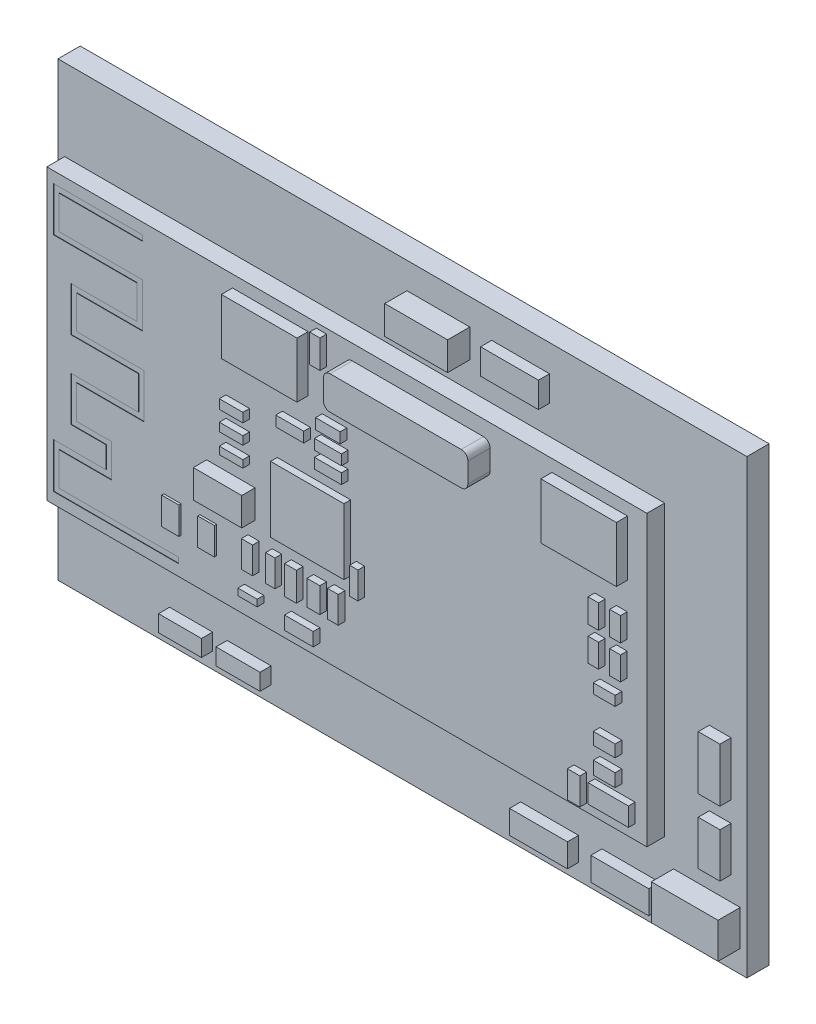
SolidWorks part; units mm, degrees
ref_plane "前视基准面" through (0, 0, 0) normal (0, 0, 1) x (1, 0, 0)
ref_plane "上视基准面" through (0, 0, 0) normal (0, 1, 0) x (1, 0, 0)
ref_plane "右视基准面" through (0, 0, 0) normal (1, 0, 0) x (0, 0, -1)
sketch "草图1" plane through (0, 0, 0) normal (0, 0, 1) x (1, 0, 0)
  line L1 (-24, -12) -> (24, -12)
  line L2 (-24, -12) -> (-24, 12)
  line L3 (-24, 12) -> (24, 12)
  line L4 (24, -12) -> (24, 12)
  line L5 (-24, -12) -> (24, 12) construction
  line L6 (-24, 12) -> (24, -12) construction
  circle A0 centre (8, 8) radius 2.1
  circle A1 centre (8, -8) radius 2.1
  point P0 (0, 0)
  dimension "D3" = 4
  dimension "D1" = 24
  dimension "D2" = 48
  dimension "D4" = 4
  dimension "D5" = 16
  dimension "D6" = 16
extrude "凸台-拉伸1" add sketch "草图1" along normal mid plane 1.6
fillet "圆角1" radius 3 4 edges at (24, 12, 0) (24, -12, 0) (-24, 12, 0) (-24, -12, 0)
sketch "草图7" plane through (0, 0, -0.8) normal (0, 0, -1) x (-1, 0, 0)
  circle A0 centre (-8, 8) radius 2.1
  circle A1 centre (-8, 8) radius 3
  circle A2 centre (-8, -8) radius 2.1
  circle A3 centre (-8, -8) radius 3
extrude "凸台-拉伸4" add sketch "草图7" along normal blind 0.01
mirror "镜向1" about plane through (0, 0, 0) normal (0, 0, 1) of "凸台-拉伸4"
sketch "草图8" plane through (0, 0, 0.8) normal (0, 0, 1) x (1, 0, 0)
  line L0 (24, -9) -> (24, 9) construction
  line L1 (-21, -12) -> (21, -12) construction
  circle A0 centre (21.46, 7) radius 0.9
  circle A1 centre (21.46, -5) radius 0.9
  dimension "D1" = 1.8
  dimension "D2" = 1.8
  dimension "D3" = 7
  dimension "D4" = 12
  dimension "D5" = 2.54
extrude "切除-拉伸4" cut sketch "草图8" against normal up to next
sketch "草图9" plane through (0, 0, 0.8) normal (0, 0, 1) x (1, 0, 0)
  line L0 (-24, 9) -> (-24, -9) construction
  line L1 (3.1, -6.5) -> (-23.9, -6.5)
  line L2 (3.1, -6.5) -> (3.1, 6.5)
  line L3 (3.1, 6.5) -> (-23.9, 6.5)
  line L4 (-23.9, -6.5) -> (-23.9, 6.5)
  line L5 (3.1, -6.5) -> (-23.9, 6.5) construction
  line L6 (3.1, 6.5) -> (-23.9, -6.5) construction
  point P0 (-10.4, 0)
  dimension "D1" = 0.1
  dimension "D2" = 27
  dimension "D3" = 13
  dimension "D4" = 0
extrude "凸台-拉伸5" add sketch "草图9" along normal blind 0.8
sketch "草图12" plane through (0, 0, 1.6) normal (0, 0, 1) x (1, 0, 0)
  line L0 (-19.605, 6) -> (-23.605, 6)
  line L1 (-23.605, 6) -> (-23.605, 4)
  line L2 (-23.605, 4) -> (-19.855, 4)
  line L3 (-19.855, 4) -> (-19.855, 2.5)
  line L4 (-19.855, 2.5) -> (-22.8189, 2.5)
  line L5 (-22.8189, 2.5) -> (-22.8189, 0.5)
  line L6 (-22.8189, 0.5) -> (-19.7832, 0.5)
  line L7 (-19.7832, 0.5) -> (-19.7832, -1)
  line L8 (-19.7832, -1) -> (-22.8189, -1)
  line L9 (-22.8189, -1) -> (-22.8189, -3)
  line L10 (-22.8189, -3) -> (-21.2355, -3)
  line L11 (-21.2355, -3) -> (-21.2355, -3.9734)
  line L12 (-21.2355, -3.9734) -> (-23.605, -3.9734)
  line L13 (-23.605, -3.9734) -> (-23.605, -6)
  line L14 (-23.605, -6) -> (-17.9828, -6)
  line L15 (-17.9828, -6) -> (-17.9828, -5.75)
  line L16 (-17.9828, -5.75) -> (-23.355, -5.75)
  line L17 (-23.355, -5.75) -> (-23.355, -4.25)
  line L18 (-23.355, -4.25) -> (-20.9855, -4.25)
  line L19 (-20.9855, -4.25) -> (-20.9855, -2.75)
  line L20 (-20.9855, -2.75) -> (-22.5689, -2.75)
  line L21 (-22.5689, -2.75) -> (-22.5689, -1.25)
  line L22 (-22.5689, -1.25) -> (-19.5257, -1.25)
  line L23 (-19.5257, -1.25) -> (-19.5257, 0.75)
  line L24 (-19.5257, 0.75) -> (-22.5689, 0.75)
  line L25 (-22.5689, 0.75) -> (-22.5689, 2.25)
  line L26 (-22.5689, 2.25) -> (-19.605, 2.25)
  line L27 (-19.605, 2.25) -> (-19.605, 4.25)
  line L28 (-19.605, 4.25) -> (-23.355, 4.25)
  line L29 (-23.355, 4.25) -> (-23.355, 5.75)
  line L30 (-23.355, 5.75) -> (-19.605, 5.75)
  line L31 (-19.605, 5.75) -> (-19.605, 6)
  line L32 (3.1, 6.5) -> (-23.9, 6.5) construction
  line L33 (-23.9, -6.5) -> (3.1, -6.5) construction
  dimension "D1" = 4
  dimension "D2" = 2
  dimension "D3" = 0.5
  dimension "D4" = 0.5
  dimension "D5" = 1.5
  dimension "D6" = 2
  dimension "D7" = 2
  dimension "D8" = 1.5
  dimension "D9" = 0.25
  dimension "D10" = 0.25
  dimension "D11" = 2
  dimension "D12" = 1.5
  dimension "D13" = 1.5
  dimension "D14" = 1.5
  dimension "D15" = 0.25
  dimension "D16" = 0.25
  dimension "D17" = 0.25
  dimension "D18" = 0.25
  dimension "D19" = 0.25
  dimension "D20" = 0.25
  dimension "D21" = 0.25
extrude "切除-拉伸5" cut sketch "草图12" against normal blind 0.02
sketch "草图13" plane through (0, 0, 1.6) normal (0, 0, 1) x (1, 0, 0)
  line L1 (-1.1732, 5.956) -> (2.2268, 5.956)
  line L2 (-1.1732, 5.956) -> (-1.1732, 3.456)
  line L3 (-1.1732, 3.456) -> (2.2268, 3.456)
  line L4 (2.2268, 5.956) -> (2.2268, 3.456)
  line L5 (-1.1732, 5.956) -> (2.2268, 3.456) construction
  line L6 (-1.1732, 3.456) -> (2.2268, 5.956) construction
  line L7 (-15.5467, 5.956) -> (-12.1467, 5.956)
  line L8 (-15.5467, 5.956) -> (-15.5467, 3.456)
  line L9 (-15.5467, 3.456) -> (-12.1467, 3.456)
  line L10 (-12.1467, 5.956) -> (-12.1467, 3.456)
  line L11 (-15.5467, 5.956) -> (-12.1467, 3.456) construction
  line L12 (-15.5467, 3.456) -> (-12.1467, 5.956) construction
  point P0 (0.5268, 4.706)
  point P5 (-13.8467, 4.706)
  dimension "D1" = 3.4
  dimension "D2" = 2.5
  dimension "D3" = 3.4
extrude "凸台-拉伸7" add sketch "草图13" along normal blind 0.5
sketch "草图14" plane through (0, 0, 1.6) normal (0, 0, 1) x (1, 0, 0)
  line L1 (-10.157, 5.8095) -> (-4.257, 5.8095)
  line L2 (-10.457, 5.5095) -> (-10.457, 4.6095)
  line L3 (-10.157, 4.3095) -> (-4.257, 4.3095)
  line L4 (-3.957, 5.5095) -> (-3.957, 4.6095)
  line L5 (-10.457, 5.8095) -> (-3.957, 4.3095) construction
  line L6 (-10.457, 4.3095) -> (-3.957, 5.8095) construction
  arc A0 (-3.957, 4.6095) -> (-4.257, 4.3095) centre (-4.257, 4.6095) cw
  arc A1 (-3.957, 5.5095) -> (-4.257, 5.8095) centre (-4.257, 5.5095) ccw
  arc A2 (-10.457, 4.6095) -> (-10.157, 4.3095) centre (-10.157, 4.6095) ccw
  arc A3 (-10.457, 5.5095) -> (-10.157, 5.8095) centre (-10.157, 5.5095) cw
  point P0 (-7.207, 5.0595)
  dimension "D3" = 0.3
  dimension "D1" = 6.5
  dimension "D2" = 1.5
extrude "凸台-拉伸8" add sketch "草图14" along normal blind 1
sketch "草图16" plane through (0, 0, -0.8) normal (0, 0, -1) x (-1, 0, 0)
  line L0 (-21, 12) -> (21, 12) construction
  line L1 (-12, 12) -> (12, 12)
  line L2 (-12, 12) -> (-12, -12)
  line L3 (-12, -12) -> (12, -12)
  line L4 (12, 12) -> (12, -12)
  line L5 (21, -12) -> (-21, -12) construction
  circle A0 centre (-8, 8) radius 3
  circle A1 centre (-8, -8) radius 3
  dimension "D1" = 24
  dimension "D2" = 12
extrude "切除-拉伸6" cut sketch "草图16" against normal blind 0.01
sketch "草图17" plane through (0, 0, 0.8) normal (0, 0, 1) x (1, 0, 0)
  line L1 (27.0686, -13.2794) -> (-27.0686, -13.2794)
  line L2 (27.0686, -13.2794) -> (27.0686, 13.2794)
  line L3 (27.0686, 13.2794) -> (-27.0686, 13.2794)
  line L4 (-27.0686, -13.2794) -> (-27.0686, 13.2794)
  line L5 (27.0686, -13.2794) -> (-27.0686, 13.2794) construction
  line L6 (27.0686, 13.2794) -> (-27.0686, -13.2794) construction
  point P0 (0, 0)
extrude "切除-拉伸7" cut sketch "草图17" against normal blind 10
sketch "草图18" plane through (0, 0, 1.6) normal (0, 0, 1) x (1, 0, 0)
  line L1 (13.9176, 12.4017) -> (4.1503, 12.4017)
  line L2 (13.9176, 12.4017) -> (13.9176, -14.7593)
  line L3 (13.9176, -14.7593) -> (4.1503, -14.7593)
  line L4 (4.1503, 12.4017) -> (4.1503, -14.7593)
extrude "切除-拉伸8" cut sketch "草图18" against normal mid plane 10
sketch "草图19" plane through (0, 0, 0.8) normal (0, 0, -1) x (-1, 0, 0)
  line L0 (23.9, 6.5) -> (23.9, -6.5) construction
  line L1 (-6.8, 10.16) -> (24.2, 10.16)
  line L2 (-6.8, 10.16) -> (-6.8, -10.16)
  line L3 (-6.8, -10.16) -> (24.2, -10.16)
  line L4 (24.2, 10.16) -> (24.2, -10.16)
  dimension "D1" = 31
  dimension "D2" = 20.32
  dimension "D3" = 10.16
  dimension "D4" = 0.3
extrude "凸台-拉伸10" add sketch "草图19" along normal blind 1
sketch "草图20" plane through (0, 0, 0.8) normal (0, 0, 1) x (1, 0, 0)
  line L0 (6.8, 10.16) -> (6.8, -10.16) construction
  line L1 (3.5, -7.56) -> (6.5, -7.56)
  line L2 (3.5, -7.56) -> (3.5, -9.16)
  line L3 (3.5, -9.16) -> (6.5, -9.16)
  line L4 (6.5, -7.56) -> (6.5, -9.16)
  line L5 (3.5, -7.56) -> (6.5, -9.16) construction
  line L6 (3.5, -9.16) -> (6.5, -7.56) construction
  line L7 (6.8, -10.16) -> (-24.2, -10.16) construction
  point P0 (5, -8.36)
  dimension "D1" = 3
  dimension "D2" = 1.6
  dimension "D3" = 0.3
  dimension "D4" = 1
extrude "凸台-拉伸11" add sketch "草图20" along normal blind 1
sketch "草图21" plane through (0, 0, 0.8) normal (0, 0, 1) x (1, 0, 0)
  line L1 (-8.4979, 8.9745) -> (-5.6692, 8.9745)
  line L2 (-8.4979, 8.9745) -> (-8.4979, 7.6948)
  line L3 (-8.4979, 7.6948) -> (-5.6692, 7.6948)
  line L4 (-5.6692, 8.9745) -> (-5.6692, 7.6948)
  line L5 (-8.4979, 8.9745) -> (-5.6692, 7.6948) construction
  line L6 (-8.4979, 7.6948) -> (-5.6692, 8.9745) construction
  point P0 (-7.0836, 8.3346)
extrude "凸台-拉伸12" add sketch "草图21" along normal blind 1
sketch "草图22" plane through (0, 0, 1.6) normal (0, 0, 1) x (1, 0, 0)
  line L1 (-13.5335, 0.3575) -> (-10.2327, 0.3575)
  line L2 (-13.5335, 0.3575) -> (-13.5335, -2.605)
  line L3 (-13.5335, -2.605) -> (-10.2327, -2.605)
  line L4 (-10.2327, 0.3575) -> (-10.2327, -2.605)
  line L5 (-9.9755, -1.9124) -> (-9.6028, -1.9124)
  line L6 (-9.9755, -1.9124) -> (-9.9755, -3.1192)
  line L7 (-9.9755, -3.1192) -> (-9.6028, -3.1192)
  line L8 (-9.6028, -1.9124) -> (-9.6028, -3.1192)
  line L9 (-14.8494, -3.3098) -> (-14.3449, -3.3098)
  line L10 (-14.8494, -3.3098) -> (-14.8494, -4.511)
  line L11 (-14.8494, -4.511) -> (-14.3449, -4.511)
  line L12 (-14.3449, -3.3098) -> (-14.3449, -4.511)
  line L13 (-13.7563, -3.3098) -> (-13.3358, -3.3098)
  line L14 (-13.7563, -3.3098) -> (-13.7563, -4.511)
  line L15 (-13.7563, -4.511) -> (-13.3358, -4.511)
  line L16 (-13.3358, -3.3098) -> (-13.3358, -4.511)
  line L17 (-12.9034, -3.3098) -> (-12.3748, -3.3098)
  line L18 (-12.9034, -3.3098) -> (-12.9034, -4.5951)
  line L19 (-12.9034, -4.5951) -> (-12.3748, -4.5951)
  line L20 (-12.3748, -3.3098) -> (-12.3748, -4.5951)
  line L21 (-11.8944, -3.3819) -> (-11.3178, -3.3819)
  line L22 (-11.8944, -3.3819) -> (-11.8944, -4.511)
  line L23 (-11.8944, -4.511) -> (-11.3178, -4.511)
  line L24 (-11.3178, -3.3819) -> (-11.3178, -4.511)
  line L25 (-10.9694, -3.3098) -> (-10.4889, -3.3098)
  line L26 (-10.9694, -3.3098) -> (-10.9694, -4.511)
  line L27 (-10.9694, -4.511) -> (-10.4889, -4.511)
  line L28 (-10.4889, -3.3098) -> (-10.4889, -4.511)
  line L29 (-12.9034, -5.3159) -> (-11.6181, -5.3159)
  line L30 (-12.9034, -5.3159) -> (-12.9034, -5.9165)
  line L31 (-12.9034, -5.9165) -> (-11.6181, -5.9165)
  line L32 (-11.6181, -5.3159) -> (-11.6181, -5.9165)
  line L33 (-15.0055, -5.3159) -> (-14.1368, -5.3159)
  line L34 (-15.0055, -5.3159) -> (-15.0055, -5.6162)
  line L35 (-15.0055, -5.6162) -> (-14.1368, -5.6162)
  line L36 (-14.1368, -5.3159) -> (-14.1368, -5.6162)
  line L37 (-16.7121, -1.3238) -> (-14.5326, -1.3238)
  line L38 (-16.7121, -1.3238) -> (-16.7121, -2.59)
  line L39 (-16.7121, -2.59) -> (-14.5326, -2.59)
  line L40 (-14.5326, -1.3238) -> (-14.5326, -2.59)
  line L41 (-15.8403, -0.2029) -> (-14.7817, -0.2029)
  line L42 (-15.8403, -0.2029) -> (-15.8403, -0.535)
  line L43 (-15.8403, -0.535) -> (-14.7817, -0.535)
  line L44 (-14.7817, -0.2029) -> (-14.7817, -0.535)
  line L45 (-15.8403, 0.7311) -> (-14.7817, 0.7311)
  line L46 (-15.8403, 0.7311) -> (-15.8403, 0.3575)
  line L47 (-15.8403, 0.3575) -> (-14.7817, 0.3575)
  line L48 (-14.7817, 0.7311) -> (-14.7817, 0.3575)
  line L49 (-15.8403, 1.6445) -> (-14.7817, 1.6445)
  line L50 (-15.8403, 1.6445) -> (-15.8403, 1.2293)
  line L51 (-15.8403, 1.2293) -> (-14.7817, 1.2293)
  line L52 (-14.7817, 1.6445) -> (-14.7817, 1.2293)
  line L53 (-11.5084, 3.0735) -> (-10.4046, 3.0735)
  line L54 (-11.5084, 3.0735) -> (-11.5084, 2.5988)
  line L55 (-11.5084, 2.5988) -> (-10.4046, 2.5988)
  line L56 (-10.4046, 3.0735) -> (-10.4046, 2.5988)
  line L57 (-11.7758, 6.2754) -> (-11.313, 6.2754)
  line L58 (-11.7758, 6.2754) -> (-11.7758, 5.0054)
  line L59 (-11.7758, 5.0054) -> (-11.313, 5.0054)
  line L60 (-11.313, 6.2754) -> (-11.313, 5.0054)
  line L61 (-11.5579, 2.2388) -> (-10.3473, 2.2388)
  line L62 (-11.5579, 2.2388) -> (-11.5579, 1.7759)
  line L63 (-11.5579, 1.7759) -> (-10.3473, 1.7759)
  line L64 (-10.3473, 2.2388) -> (-10.3473, 1.7759)
  line L65 (-11.5579, 1.5029) -> (-10.3473, 1.5029)
  line L66 (-11.5579, 1.5029) -> (-11.5579, 1.04)
  line L67 (-11.5579, 1.04) -> (-10.3473, 1.04)
  line L68 (-10.3473, 1.5029) -> (-10.3473, 1.04)
  line L69 (-13.3006, 2.2783) -> (-12.0425, 2.2783)
  line L70 (-13.3006, 2.2783) -> (-13.3006, 1.8155)
  line L71 (-13.3006, 1.8155) -> (-12.0425, 1.8155)
  line L72 (-12.0425, 2.2783) -> (-12.0425, 1.8155)
extrude "凸台-拉伸13" add sketch "草图22" along normal blind 0.3
sketch "草图23" plane through (0, 0, 0.8) normal (0, 0, 1) x (1, 0, 0)
  line L1 (0.2784, -8.3892) -> (2.8836, -8.3892)
  line L2 (0.2784, -8.3892) -> (0.2784, -9.4436)
  line L3 (0.2784, -9.4436) -> (2.8836, -9.4436)
  line L4 (2.8836, -8.3892) -> (2.8836, -9.4436)
  line L5 (-3.3812, -8.3892) -> (-0.776, -8.3892)
  line L6 (-3.3812, -8.3892) -> (-3.3812, -9.4436)
  line L7 (-3.3812, -9.4436) -> (-0.776, -9.4436)
  line L8 (-0.776, -8.3892) -> (-0.776, -9.4436)
  line L9 (-19.177, -8.7001) -> (-17.2428, -8.7001)
  line L10 (-19.177, -8.7001) -> (-19.177, -9.4436)
  line L11 (-19.177, -9.4436) -> (-17.2428, -9.4436)
  line L12 (-17.2428, -8.7001) -> (-17.2428, -9.4436)
  line L13 (-16.5884, -8.7001) -> (-14.6106, -8.7001)
  line L14 (-16.5884, -8.7001) -> (-16.5884, -9.4436)
  line L15 (-16.5884, -9.4436) -> (-14.6106, -9.4436)
  line L16 (-14.6106, -8.7001) -> (-14.6106, -9.4436)
  line L17 (-4.6837, 8.9474) -> (-2.0786, 8.9474)
  line L18 (-4.6837, 8.9474) -> (-4.6837, 7.7999)
  line L19 (-4.6837, 7.7999) -> (-2.0786, 7.7999)
  line L20 (-2.0786, 8.9474) -> (-2.0786, 7.7999)
  line L21 (5.1084, -1.154) -> (6.0866, -1.154)
  line L22 (5.1084, -1.154) -> (5.1084, -3.5737)
  line L23 (5.1084, -3.5737) -> (6.0866, -3.5737)
  line L24 (6.0866, -1.154) -> (6.0866, -3.5737)
  line L25 (5.1084, -4.49) -> (6.0866, -4.49)
  line L26 (5.1084, -4.49) -> (5.1084, -6.4939)
  line L27 (5.1084, -6.4939) -> (6.0866, -6.4939)
  line L28 (6.0866, -4.49) -> (6.0866, -6.4939)
extrude "凸台-拉伸14" add sketch "草图23" along normal blind 0.5
sketch "草图24" plane through (0, 0, 1.9) normal (0, 0, 1) x (1, 0, 0)
  line L4 (-16.7121, -1.3238) -> (-16.7121, -2.59)
  line L5 (-16.7121, -2.59) -> (-14.5326, -2.59)
  line L6 (-14.5326, -2.59) -> (-14.5326, -1.3238)
  line L7 (-14.5326, -1.3238) -> (-16.7121, -1.3238)
  line L8 (-16.7121, -1.3238) -> (-16.7121, -2.59)
  line L9 (-16.7121, -2.59) -> (-14.5326, -2.59)
  line L10 (-14.5326, -2.59) -> (-14.5326, -1.3238)
  line L11 (-14.5326, -1.3238) -> (-16.7121, -1.3238)
  dimension "D1" = 0
extrude "凸台-拉伸15" add sketch "草图24" along normal blind 0.3
sketch "草图25" plane through (0, 0, 1.6) normal (0, 0, 1) x (1, 0, 0)
  line L1 (-17.0133, -3.6093) -> (-16.2634, -3.6093)
  line L2 (-17.0133, -3.6093) -> (-17.0133, -4.8364)
  line L3 (-17.0133, -4.8364) -> (-16.2634, -4.8364)
  line L4 (-16.2634, -3.6093) -> (-16.2634, -4.8364)
  line L5 (-18.6358, -3.6093) -> (-17.8586, -3.6093)
  line L6 (-18.6358, -3.6093) -> (-18.6358, -4.8364)
  line L7 (-18.6358, -4.8364) -> (-17.8586, -4.8364)
  line L8 (-17.8586, -3.6093) -> (-17.8586, -4.8364)
extrude "凸台-拉伸16" add sketch "草图25" along normal blind 0.1
sketch "草图26" plane through (0, 0, 1.6) normal (0, 0, 1) x (1, 0, 0)
  line L1 (0.7524, 2.2194) -> (1.2229, 2.2194)
  line L2 (0.7524, 2.2194) -> (0.7524, 1.1487)
  line L3 (0.7524, 1.1487) -> (1.2229, 1.1487)
  line L4 (1.2229, 2.2194) -> (1.2229, 1.1487)
  line L5 (1.7258, 2.2194) -> (2.2125, 2.2194)
  line L6 (1.7258, 2.2194) -> (1.7258, 1.1487)
  line L7 (1.7258, 1.1487) -> (2.2125, 1.1487)
  line L8 (2.2125, 2.2194) -> (2.2125, 1.1487)
  line L9 (0.7524, 0.6864) -> (1.2229, 0.6864)
  line L10 (0.7524, 0.6864) -> (0.7524, -0.3681)
  line L11 (0.7524, -0.3681) -> (1.2229, -0.3681)
  line L12 (1.2229, 0.6864) -> (1.2229, -0.3681)
  line L13 (1.7258, 0.6864) -> (2.2125, 0.6864)
  line L14 (1.7258, 0.6864) -> (1.7258, -0.3681)
  line L15 (1.7258, -0.3681) -> (2.2125, -0.3681)
  line L16 (2.2125, 0.6864) -> (2.2125, -0.3681)
  line L17 (0.9877, -1.0089) -> (1.9691, -1.0089)
  line L18 (0.9877, -1.0089) -> (0.9877, -1.4469)
  line L19 (0.9877, -1.4469) -> (1.9691, -1.4469)
  line L20 (1.9691, -1.0089) -> (1.9691, -1.4469)
  line L21 (0.9877, -2.9052) -> (1.9691, -2.9052)
  line L22 (0.9877, -2.9052) -> (0.9877, -3.4476)
  line L23 (0.9877, -3.4476) -> (1.9691, -3.4476)
  line L24 (1.9691, -2.9052) -> (1.9691, -3.4476)
  line L25 (0.9877, -4.0266) -> (1.9691, -4.0266)
  line L26 (0.9877, -4.0266) -> (0.9877, -4.6104)
  line L27 (0.9877, -4.6104) -> (1.9691, -4.6104)
  line L28 (1.9691, -4.0266) -> (1.9691, -4.6104)
  line L29 (0.7524, -5.0226) -> (2.5702, -5.0226)
  line L30 (0.7524, -5.0226) -> (0.7524, -5.8583)
  line L31 (0.7524, -5.8583) -> (2.5702, -5.8583)
  line L32 (2.5702, -5.0226) -> (2.5702, -5.8583)
  line L33 (-0.1775, -4.9425) -> (0.3835, -4.9425)
  line L34 (-0.1775, -4.9425) -> (-0.1775, -6.156)
  line L35 (-0.1775, -6.156) -> (0.3835, -6.156)
  line L36 (0.3835, -4.9425) -> (0.3835, -6.156)
extrude "凸台-拉伸17" add sketch "草图26" along normal blind 0.3
